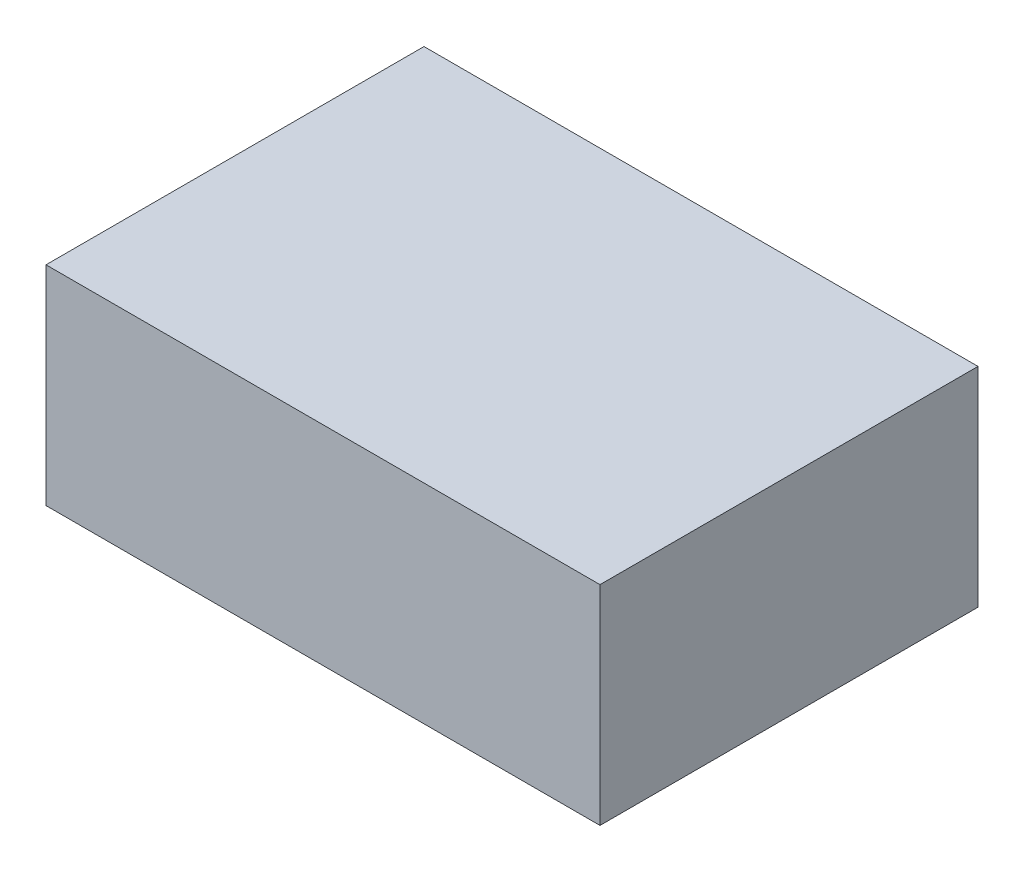
SolidWorks part; units mm, degrees
ref_plane "前视基准面" through (0, 0, 0) normal (0, 0, 1) x (1, 0, 0)
ref_plane "上视基准面" through (0, 0, 0) normal (0, 1, 0) x (1, 0, 0)
ref_plane "右视基准面" through (0, 0, 0) normal (1, 0, 0) x (0, 0, -1)
other "Configuration Table"
sketch "草图1" plane through (0, 0, 0) normal (0, 1, 0) x (1, 0, 0)
  line L1 (0, 58) -> (85, 58)
  line L2 (0, 58) -> (0, 0)
  line L3 (0, 0) -> (85, 0)
  line L4 (85, 58) -> (85, 0)
  point P4 (0, 0)
  dimension "D1" = 85
  dimension "D2" = 58
extrude "凸台-拉伸1" add sketch "草图1" along normal blind 32
